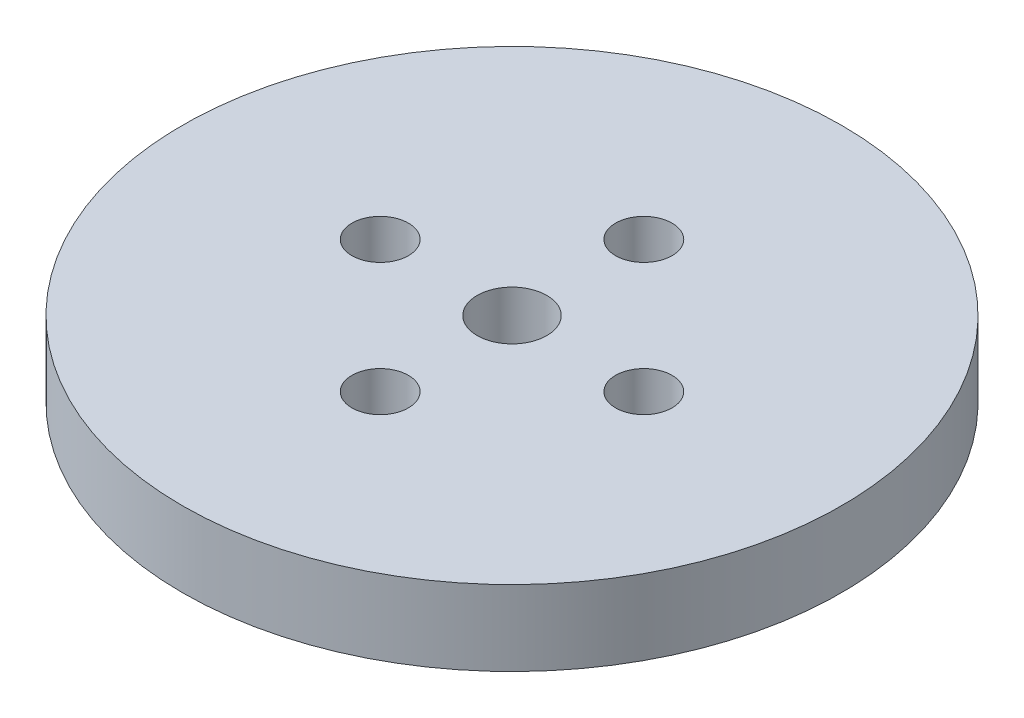
SolidWorks part; units mm, degrees
ref_plane "Front Plane" through (0, 0, 0) normal (0, 0, 1) x (1, 0, 0)
ref_plane "Top Plane" through (0, 0, 0) normal (0, 1, 0) x (1, 0, 0)
ref_plane "Right Plane" through (0, 0, 0) normal (1, 0, 0) x (0, 0, -1)
sketch "Sketch1" plane through (0, 0, 0) normal (0, 1, 0) x (1, 0, 0)
  circle A0 centre (0, 0) radius 17.5
  circle A1 centre (0, 0) radius 1.85
  circle A2 centre (0, 0) radius 7 construction
  circle A3 centre (-7, 0) radius 1.5
  circle A4 centre (0, 7) radius 1.5
  circle A5 centre (7, 0) radius 1.5
  circle A6 centre (0, -7) radius 1.5
  point P16 (0, 0)
  dimension "D1" = 35
  dimension "D2" = 3.7
  dimension "D3" = 14
  dimension "D4" = 3
  dimension "D5" = 4
extrude "Boss-Extrude1" add sketch "Sketch1" along normal blind 4
